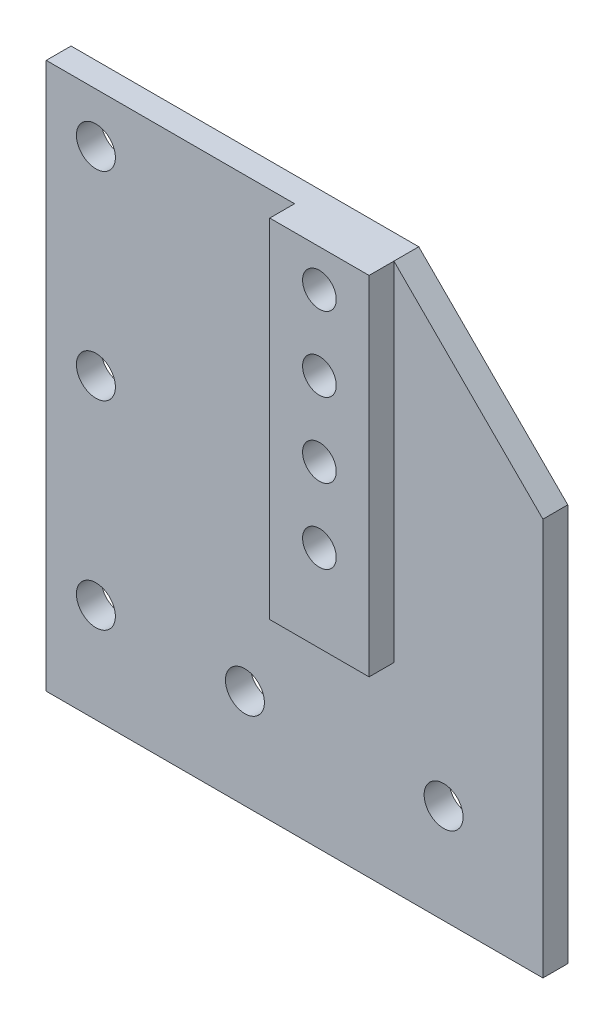
SolidWorks part; units mm, degrees
material "6061 Alloy"
ref_plane "Front Plane" through (0, 0, 0) normal (0, 0, 1) x (1, 0, 0)
ref_plane "Top Plane" through (0, 0, 0) normal (0, 1, 0) x (1, 0, 0)
ref_plane "Right Plane" through (0, 0, 0) normal (1, 0, 0) x (0, 0, -1)
sketch "Sketch1" plane through (0, 0, 0) normal (0, 0, 1) x (1, 0, 0)
  line L0 (-254, -12.7) -> (-266.7, -12.7)
  line L2 (-266.7, 57.15) -> (-254, 57.15)
  line L3 (-254, -16.7024) -> (-254, 609.6) construction
  line L4 (-254, -12.7) -> (-203.2, -12.7)
  line L5 (-254, 57.15) -> (-222.25, 57.15)
  line L6 (-203.2, -12.7) -> (-203.2, 12.7)
  line L7 (-254, 12.7) -> (-161.798, 12.7) construction
  line L13 (-222.25, 57.15) -> (-203.2, 38.1)
  line L15 (-266.7, -12.7) -> (-266.7, 57.15)
  line L16 (-266.7, 609.6) -> (-266.7, -16.7024) construction
  line L17 (-203.2, 12.7) -> (-203.2, 38.1)
  dimension "D1" = 69.85
  dimension "D2" = 25.4
  dimension "D3" = 31.75
extrude "Boss-Extrude1" add sketch "Sketch1" along normal blind 3.175
sketch "Sketch2" plane through (0, 0, 3.175) normal (0, 0, 1) x (1, 0, 0)
  line L0 (-203.2, -12.7) -> (-203.2, 12.7) construction
  line L1 (-215.9, 0) -> (-241.3, 0) construction
  line L2 (-203.2, 0) -> (-215.9, 0) construction
  line L3 (-254, -12.7) -> (-266.7, -12.7) construction
  line L4 (-260.35, -12.7) -> (-260.35, 0) construction
  line L5 (-260.35, 0) -> (-260.35, 25.4) construction
  line L6 (-260.35, 25.4) -> (-260.35, 50.7989) construction
  line L7 (-260.35, 25.4) -> (-260.35, 50.8) construction
  line L8 (-254, 12.7) -> (-161.798, 12.7) construction
  dimension "D1" = 12.7
  dimension "D2" = 25.4
  dimension "D3" = 12.7
  dimension "D4" = 25.4
  dimension "D5" = 25.3989
hole_wizard "#10 Clearance Hole1" positions "Sketch3" profile "Sketch4" hole size "#10" standard "ANSI Inch" end condition through all
sketch "Sketch3" plane through (0, 0, 3.175) normal (0, 0, 1) x (1, 0, 0)
  point P15 (-260.35, 50.7989)
  point P18 (-260.35, 25.4)
  point P21 (-260.35, 0)
  point P24 (-241.3, 0)
  point P27 (-215.9, 0)
sketch "Sketch4" plane through (-260.35, 50.7989, 3.175) normal (1, 0, 0) x (0, -1, 0)
  line L0 (0, 0) -> (0, 3.175)
  line L1 (0, 3.175) -> (2.4892, 3.175)
  line L2 (2.4892, 3.175) -> (2.4892, 0)
  line L5 (2.4892, 0) -> (0, 0)
  line L11 (0, -6.35) -> (0, 107.95) construction
  dimension "Thru Hole Dia." = 4.9784
  dimension "Thru Hole Depth" = 3.175
sketch "Sketch5" plane through (0, 0, 3.175) normal (0, 0, 1) x (1, 0, 0)
  line L0 (-222.25, 57.15) -> (-222.25, 50.8) construction
  line L1 (-222.25, 57.15) -> (-234.95, 57.15)
  line L3 (-234.95, 57.15) -> (-234.95, 12.7)
  line L4 (-222.25, 50.8) -> (-222.25, 12.7)
  line L5 (-222.25, 12.7) -> (-234.95, 12.7)
  line L6 (-222.25, 50.8) -> (-222.25, 57.15)
  line L7 (-222.25, 57.15) -> (-266.7, 57.15) construction
  point P7 (-222.25, 50.8)
  dimension "D3" = 38.1
extrude "Boss-Extrude2" add sketch "Sketch5" along normal blind 3.175
sketch "Sketch6" plane through (0, 0, 6.35) normal (0, 0, 1) x (1, 0, 0)
  line L0 (-228.6, 57.15) -> (-228.6, 52.3875) construction
  line L1 (-228.6, 52.3875) -> (-228.6, 42.8625) construction
  line L2 (-228.6, 42.8625) -> (-228.6, 33.3375) construction
  line L3 (-222.25, 57.15) -> (-234.95, 57.15) construction
  line L4 (-228.6, 33.3375) -> (-228.6, 23.8125) construction
  dimension "D1" = 9.525
  dimension "D2" = 4.7625
  dimension "D3" = 9.525
  dimension "D4" = 9.525
hole_wizard "#8 Clearance Hole1" positions "Sketch7" profile "Sketch8" hole size "#8" standard "ANSI Inch" end condition through all
sketch "Sketch7" plane through (0, 0, 6.35) normal (0, 0, 1) x (1, 0, 0)
  point P0 (-228.6, 42.8625)
  point P3 (-228.6, 52.3875)
  point P7 (-228.6, 33.3375)
  point P10 (-228.6, 23.8125)
sketch "Sketch8" plane through (-228.6, 42.8625, 6.35) normal (1, 0, 0) x (0, -1, 0)
  line L0 (0, 0) -> (0, 6.35)
  line L1 (0, 6.35) -> (2.1526, 6.35)
  line L2 (2.1526, 6.35) -> (2.1526, 0)
  line L5 (2.1526, 0) -> (0, 0)
  line L11 (0, -6.35) -> (0, 107.95) construction
  dimension "Thru Hole Dia." = 4.3053
  dimension "Thru Hole Depth" = 6.35
